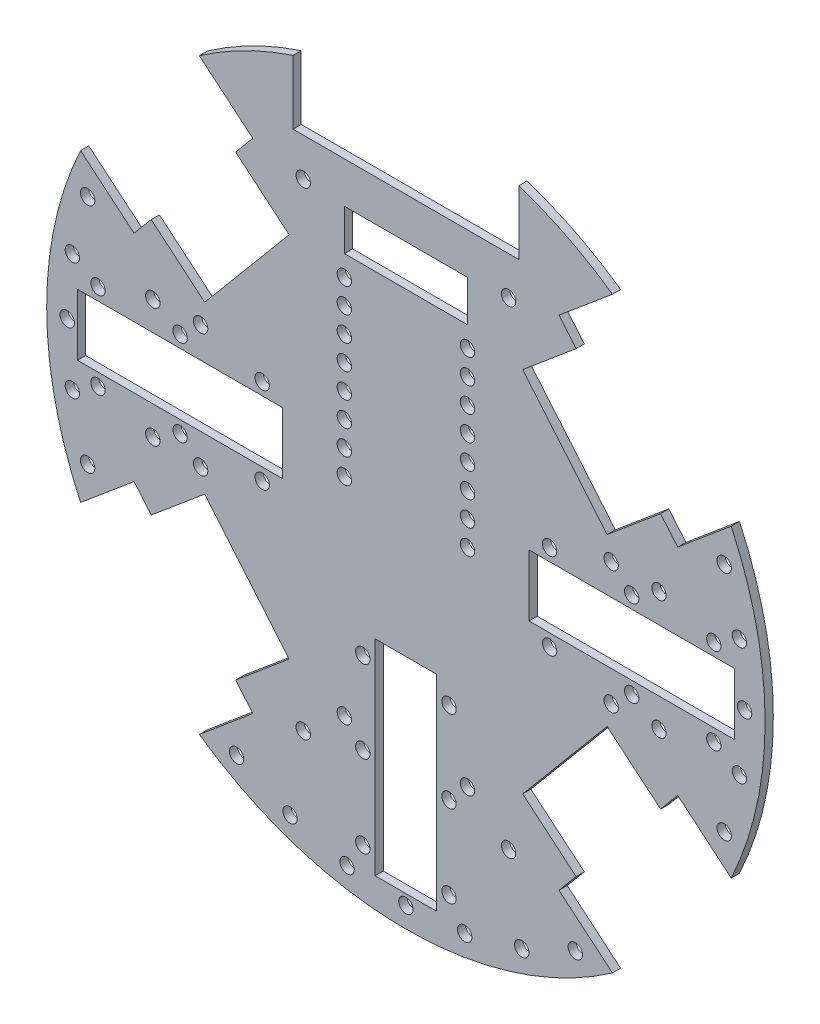
SolidWorks part; units mm, degrees
ref_plane "Front Plane" through (0, 0, 0) normal (0, 0, 1) x (1, 0, 0)
ref_plane "Top Plane" through (0, 0, 0) normal (0, 1, 0) x (1, 0, 0)
ref_plane "Right Plane" through (0, 0, 0) normal (1, 0, 0) x (0, 0, -1)
sketch "Sketch1" plane through (0, 0, 0) normal (0, 0, 1) x (1, 0, 0)
  circle A1 centre (0, 0) radius 87.5
  dimension "D1" = 87.5
extrude "Boss-Extrude1" add sketch "Sketch1" against normal blind 2
sketch "Sketch3" plane through (0, 0, 0) normal (0, 0, 1) x (1, 0, 0)
  line L0 (-87.5, 0) -> (0, 0) construction
  line L1 (0, 0) -> (-38.7294, 32.4978) construction
  line L2 (-49.014, 20.2411) -> (-28.4448, 44.7546)
  line L3 (-49.014, 20.2411) -> (-62.0368, 31.1685)
  line L4 (-62.0368, 31.1685) -> (-66.2149, 26.1892)
  line L5 (-66.2149, 26.1892) -> (-79.2377, 37.1166)
  line L6 (-79.2377, 37.1166) -> (-50.3122, 71.5886) construction
  line L7 (-50.3122, 71.5886) -> (-37.2895, 60.6612)
  line L8 (-37.2895, 60.6612) -> (-41.4676, 55.6819)
  line L9 (-41.4676, 55.6819) -> (-28.4448, 44.7546)
  line L10 (-62.0368, 31.1685) -> (-41.4676, 55.6819) construction
  line L11 (-38.7294, 32.4978) -> (-51.7522, 43.4252) construction
  line L12 (-51.7522, 43.4252) -> (-64.7749, 54.3526) construction
  line L13 (-61.6451, 14.5223) -> (-25.0062, 58.1868) construction
  circle A0 centre (0, 0) radius 87.5 construction
  arc A1 (-50.3122, 71.5886) -> (-79.2377, 37.1166) centre (0, 0) ccw
  arc A2 (-87.5, 0) -> (87.5, 0) centre (0, 0) ccw
  circle A3 centre (-61.6451, 14.5223) radius 1.75
  circle A4 centre (-25.0062, 58.1868) radius 1.75
  point P19 (-43.3257, 36.3546)
  circle M14 centre (0, 0) radius 87.5
  dimension "D8" = 3.5
  dimension "D1" = 40
  dimension "D2" = 32
  dimension "D3" = 45
  dimension "D4" = 17
  dimension "D5" = 17
  dimension "D6" = 57
  dimension "D7" = 6
extrude "Cut-Extrude1" cut sketch "Sketch3" against normal through all contours L9 L8 L7 L5 L4 L3 L2 M14 | A3 | A4
mirror "Mirror1" about plane through (0, 0, 0) normal (1, 0, 0) of "Cut-Extrude1" second plane through (0, 0, 0) second plane normal (0, 1, 0)
sketch "Sketch4" plane through (0, 0, 0) normal (0, 0, 1) x (1, 0, 0)
  line L1 (-27.5, 107.5) -> (27.5, 107.5)
  line L2 (-27.5, 107.5) -> (-27.5, 67.5)
  line L3 (-27.5, 67.5) -> (27.5, 67.5)
  line L4 (27.5, 107.5) -> (27.5, 67.5)
  line L5 (-27.5, 107.5) -> (27.5, 67.5) construction
  line L6 (-27.5, 67.5) -> (27.5, 107.5) construction
  arc A0 (50.3122, 71.5886) -> (-50.3122, 71.5886) centre (0, 0) ccw construction
  point P0 (0, 87.5)
  dimension "D1" = 55
  dimension "D2" = 40
extrude "Cut-Extrude2" cut sketch "Sketch4" against normal through all and the other way through all
sketch "Sketch5" plane through (0, 0, 0) normal (0, 0, 1) x (1, 0, 0)
  line L0 (0, 0) -> (-50, 0) construction
  line L1 (-50, 15) -> (-50, -15) construction
  circle A0 centre (-50, 15) radius 1.75
  circle A1 centre (-50, -15) radius 1.75
  dimension "D1" = 3.5
  dimension "D2" = 30
  dimension "D3" = 50
extrude "Cut-Extrude3" cut sketch "Sketch5" against normal through all
sketch "Sketch8" plane through (0, 0, 0) normal (0, 0, 1) x (1, 0, 0)
  line L0 (-30, 0) -> (0, 0) construction
  line L1 (-80, 7.5) -> (-30, 7.5)
  line L2 (-80, 7.5) -> (-80, -7.5)
  line L3 (-80, -7.5) -> (-30, -7.5)
  line L4 (-30, 7.5) -> (-30, -7.5)
  line L5 (-80, 7.5) -> (-30, -7.5) construction
  line L6 (-80, -7.5) -> (-30, 7.5) construction
  point P0 (-55, 0)
  dimension "D1" = 30
  dimension "D2" = 50
  dimension "D3" = 15
extrude "Cut-Extrude4" cut sketch "Sketch8" against normal through all
sketch "Sketch9" plane through (0, 0, 0) normal (0, 0, 1) x (1, 0, 0)
  line L0 (-35, 10.5) -> (-35, -10.5) construction
  line L1 (-35, 0) -> (-30, 0) construction
  line L2 (-30, -7.5) -> (-30, 7.5) construction
  circle A0 centre (-35, 10.5) radius 1.75
  circle A1 centre (-35, -10.5) radius 1.75
  circle A2 centre (-55, 10.5) radius 1.75
  circle A3 centre (-55, -10.5) radius 1.75
  circle A4 centre (-75, 10.5) radius 1.75
  circle A5 centre (-75, -10.5) radius 1.75
  dimension "D2" = 3.5
  dimension "D1" = 21
  dimension "D3" = 5
  dimension "D5" = 20
  dimension "D4" = 3
extrude "Cut-Extrude5" cut sketch "Sketch9" against normal through all
pattern_circular "CirPattern1" count 3 every 90 about axis through (0, 0, 0) along (0, 0, 1) of "Cut-Extrude3", "Cut-Extrude4", "Cut-Extrude5"
sketch "Sketch10" plane through (0, 0, 0) normal (0, 0, 1) x (1, 0, 0)
  line L0 (0, 47.5) -> (0, 0) construction
  line L1 (-15, 57.5) -> (15, 57.5)
  line L2 (-15, 57.5) -> (-15, 47.5)
  line L3 (-15, 47.5) -> (15, 47.5)
  line L4 (15, 57.5) -> (15, 47.5)
  line L5 (-15, 57.5) -> (15, 47.5) construction
  line L6 (-15, 47.5) -> (15, 57.5) construction
  line L7 (-27.5, 67.5) -> (27.5, 67.5) construction
  point P0 (0, 52.5)
  dimension "D1" = 30
  dimension "D2" = 10
  dimension "D3" = 10
extrude "Cut-Extrude6" cut sketch "Sketch10" against normal through all
sketch "Sketch11" plane through (0, 0, 0) normal (0, 0, 1) x (1, 0, 0)
  line L0 (-15, 42.5) -> (15, 42.5) construction
  line L1 (0, 42.5) -> (0, 47.5) construction
  line L2 (-15, 47.5) -> (15, 47.5) construction
  circle A0 centre (-15, 42.5) radius 1.75
  circle A1 centre (15, 42.5) radius 1.75
  circle A2 centre (-15, 36.5) radius 1.75
  circle A3 centre (15, 36.5) radius 1.75
  circle A4 centre (-15, 30.5) radius 1.75
  circle A5 centre (15, 30.5) radius 1.75
  circle A6 centre (-15, 24.5) radius 1.75
  circle A7 centre (15, 24.5) radius 1.75
  circle A8 centre (-15, 18.5) radius 1.75
  circle A9 centre (15, 18.5) radius 1.75
  circle A10 centre (-15, 12.5) radius 1.75
  circle A11 centre (15, 12.5) radius 1.75
  circle A12 centre (-15, 6.5) radius 1.75
  circle A13 centre (15, 6.5) radius 1.75
  circle A14 centre (-15, 0.5) radius 1.75
  circle A15 centre (15, 0.5) radius 1.75
  dimension "D3" = 3.5
  dimension "D1" = 30
  dimension "D2" = 5
  dimension "D4" = 8
extrude "Cut-Extrude7" cut sketch "Sketch11" against normal through all
sketch "Sketch12" plane through (0, 0, 0) normal (0, 0, 1) x (1, 0, 0)
  line L0 (-87.5, 0) -> (0, 0) construction
  line L1 (0, 0) -> (-77.5246, 28.2167) construction
  line L2 (0, 0) -> (-77.5246, 28.2167) construction
  line L3 (0, 0) -> (-81.2466, 14.326) construction
  arc A0 (-79.2377, 37.1166) -> (-79.2377, -37.1166) centre (0, 0) ccw construction
  circle A1 centre (-77.5246, 28.2167) radius 1.75
  circle A2 centre (-81.2466, 14.326) radius 1.75
  circle A3 centre (-82.5, 0) radius 1.75
  circle A4 centre (-81.2466, -14.326) radius 1.75
  circle A5 centre (-77.5246, -28.2167) radius 1.75
  dimension "D3" = 3.5
  dimension "D1" = 20
  dimension "D2" = 82.5
  dimension "D5" = 10
  dimension "D4" = 5
extrude "Cut-Extrude8" cut sketch "Sketch12" against normal through all
mirror "Mirror2" about plane through (0, 0, 0) normal (1, 0, 0) of "Cut-Extrude8"
sketch "Sketch13" plane through (0, 0, 0) normal (0, 0, 1) x (1, 0, 0)
  line L0 (0, -87.5) -> (0, 0) construction
  line L1 (0, 0) -> (-41.25, -71.4471) construction
  line L2 (0, 0) -> (-41.25, -71.4471) construction
  line L3 (0, 0) -> (-28.2167, -77.5246) construction
  arc A0 (-50.3122, -71.5886) -> (50.3122, -71.5886) centre (0, 0) ccw construction
  circle A1 centre (-41.25, -71.4471) radius 1.75
  circle A2 centre (-28.2167, -77.5246) radius 1.75
  circle A3 centre (-14.326, -81.2466) radius 1.75
  circle A4 centre (0, -82.5) radius 1.75
  circle A5 centre (14.326, -81.2466) radius 1.75
  circle A6 centre (28.2167, -77.5246) radius 1.75
  circle A7 centre (41.25, -71.4471) radius 1.75
  dimension "D3" = 3.5
  dimension "D1" = 30
  dimension "D2" = 82.5
  dimension "D5" = 10
  dimension "D4" = 7
extrude "Cut-Extrude9" cut sketch "Sketch13" against normal through all
